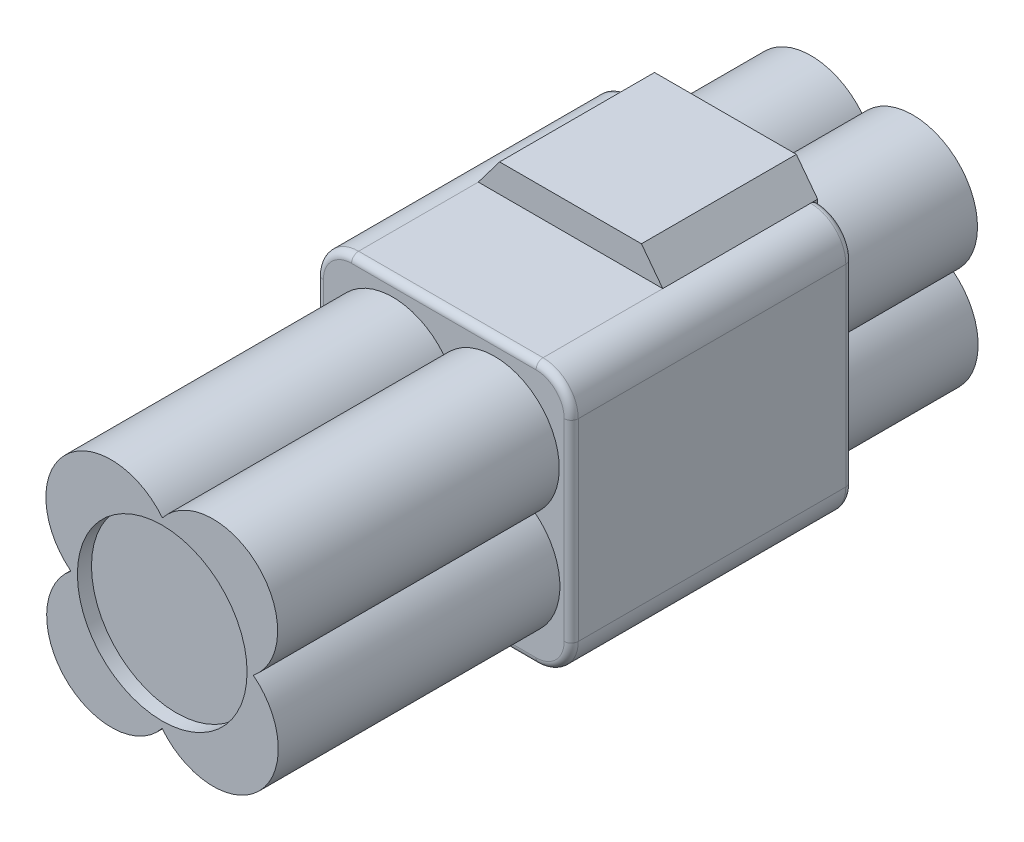
SolidWorks part; units mm, degrees
ref_plane "正面" through (0, 0, 0) normal (0, 0, 1) x (1, 0, 0)
ref_plane "平面" through (0, 0, 0) normal (0, 1, 0) x (1, 0, 0)
ref_plane "右側面" through (0, 0, 0) normal (1, 0, 0) x (0, 0, -1)
sketch "ｽｹｯﾁ1" plane through (0, 0, 0) normal (0, 0, 1) x (1, 0, 0)
  line L1 (0, 0) -> (18.1, 0)
  line L2 (0, 0) -> (0, 18.7)
  line L3 (0, 18.7) -> (18.1, 18.7)
  line L4 (18.1, 0) -> (18.1, 18.7)
  dimension "D1" = 18.7
  dimension "D2" = 18.1
extrude "ﾎﾞｽ - 押し出し1" add sketch "ｽｹｯﾁ1" along normal blind 20
sketch "ｽｹｯﾁ2" plane through (0, 18.7, 0) normal (0, 1, 0) x (1, 0, 0)
  line L0 (9.05, 0) -> (9.05, -20) construction
  line L1 (18.1, 0) -> (0, 0) construction
  line L2 (18.1, -20) -> (0, -20) construction
  line L3 (2.5, 0) -> (2.5, -11)
  line L4 (2.5, -11) -> (15.6, -11)
  line L5 (15.6, -11) -> (15.6, 0)
  line L6 (15.6, 0) -> (2.5, 0)
  line L7 (0, -20) -> (0, 0) construction
  line L8 (18.1, -20) -> (18.1, 0) construction
  dimension "D1" = 2.5
  dimension "D2" = 2.5
  dimension "D3" = 11
extrude "ﾎﾞｽ - 押し出し2" add sketch "ｽｹｯﾁ2" along normal blind 2
sketch "ｽｹｯﾁ3" plane through (0, 0, 0) normal (0, 0, -1) x (-1, 0, 0)
  arc A0 (-9.0649, 15.8319) -> (-15.5212, 9.3819) centre (-12.6581, 12.9723) ccw
  arc A5 (-2.5663, 9.311) -> (-9.0649, 15.8319) centre (-5.4277, 12.9581) ccw
  arc A6 (-15.5212, 9.3819) -> (-9.045, 2.8769) centre (-12.6723, 5.7419) ccw
  arc A7 (-9.045, 2.8769) -> (-3.4854, 9.8848) centre (-5.4419, 5.7277) ccw
  point P3 (-0.8474, 5.7277)
  point P5 (-9.2083, 6.801)
  point P7 (-2.0045, 6.7786)
  point P8 (-9.2229, 14.0226)
  point P10 (-8.0659, 12.9723)
  point P12 (-0.7921, 12.9581)
  point P15 (-1.951, 14.021)
  point P16 (-5.4277, 12.9581)
  point P17 (-12.6581, 12.9723)
  point P18 (-12.6723, 5.7419)
  point P19 (-5.4419, 5.7277)
  point P25 (-8.05, 5.7419)
extrude "ﾎﾞｽ - 押し出し3" add sketch "ｽｹｯﾁ3" along normal blind 9.7 and the other way blind 40
fillet "ﾌｨﾚｯﾄ1" radius 2.5 4 edges at (0, 0, 10) (18.1, 0, 10) (18.1, 18.7, 10) (0, 18.7, 10)
fillet "ﾌｨﾚｯﾄ2" radius 0.5 15 edges at (0.7322, 17.9678, 20) (9.05, 18.7, 20) (17.3678, 17.9678, 20) (18.1, 9.35, 20) (17.3678, 0.7322, 20) (9.05, 0, 20) (0.7322, 0.7322, 20) (18.1, 9.35, 0) (17.3678, 0.7322, 0) (9.05, 0, 0) (0.7322, 0.7322, 0) (0, 9.35, 0) (0, 9.35, 20)
sketch "ｽｹｯﾁ4" plane through (0, 0, 0) normal (0, 0, -1) x (-1, 0, 0)
  line L0 (-15.6, 18.7) -> (-14.0859, 20.7)
  line L1 (-15.6, 20.7) -> (-2.5, 20.7) construction
  line L2 (-14.0859, 20.7) -> (-15.6, 20.7)
  line L3 (-15.6, 20.7) -> (-15.6, 18.7)
  line L4 (-9.05, 20.7) -> (-9.05, 15.5953) construction
  line L5 (-2.5, 20.7) -> (-2.5, 18.7)
  line L6 (-4.0141, 20.7) -> (-2.5, 20.7)
  line L7 (-2.5, 18.7) -> (-4.0141, 20.7)
extrude "ｶｯﾄ - 押し出し1" cut sketch "ｽｹｯﾁ4" against normal through all
sketch "ｽｹｯﾁ5" plane through (0, 0, -9.7) normal (0, 0, -1) x (-1, 0, 0)
  line L0 (-9.0649, 15.8319) -> (-9.045, 2.8769) construction
  arc A0 (-15.5212, 9.3819) -> (-9.045, 2.8769) centre (-12.6723, 5.7419) ccw construction
  arc A1 (-15.5212, 9.3819) -> (-9.045, 2.8769) centre (-12.6723, 5.7419) ccw construction
  circle A2 centre (-9.055, 9.3544) radius 6.1058
extrude "ｶｯﾄ - 押し出し2" cut sketch "ｽｹｯﾁ5" against normal blind 1
sketch "ｽｹｯﾁ6" plane through (0, 0, 40) normal (0, 0, 1) x (1, 0, 0)
  line L0 (9.0649, 15.8319) -> (9.045, 2.8769) construction
  circle A0 centre (9.055, 9.3544) radius 6.0247
extrude "ｶｯﾄ - 押し出し3" cut sketch "ｽｹｯﾁ6" against normal blind 1
